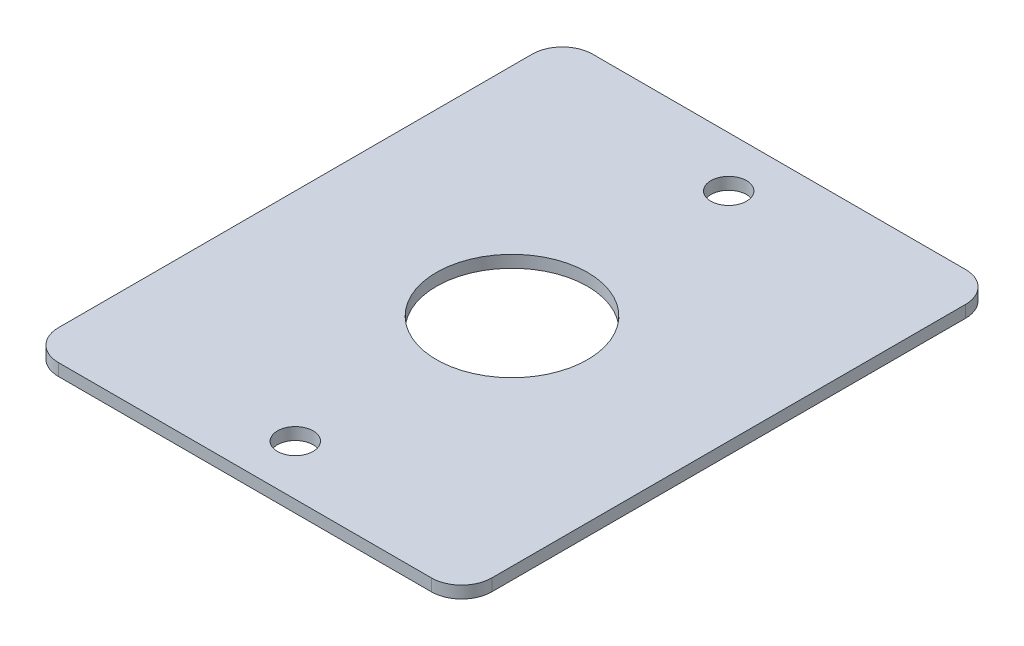
SolidWorks part; units mm, degrees
material "6061-T6 (SS)"
ref_plane "Front Plane" through (0, 0, 0) normal (0, 0, 1) x (1, 0, 0)
ref_plane "Top Plane" through (0, 0, 0) normal (0, 1, 0) x (1, 0, 0)
ref_plane "Right Plane" through (0, 0, 0) normal (1, 0, 0) x (0, 0, -1)
sketch "Sketch1" plane through (0, 0, 0) normal (0, 1, 0) x (1, 0, 0)
  line L0 (-27.305, 33.655) -> (-27.305, -33.655)
  line L1 (-27.305, 33.655) -> (27.305, 33.655)
  line L2 (-27.305, -33.655) -> (27.305, -33.655)
  line L3 (27.305, 33.655) -> (27.305, -33.655)
  line L4 (-27.305, -33.655) -> (27.305, 33.655) construction
  line L5 (0, -27.305) -> (0, 27.305) construction
  circle A0 centre (0, 0) radius 9.525
  circle A1 centre (0, 27.305) radius 2.2479
  circle A2 centre (0, -27.305) radius 2.2479
  dimension "D1" = 19.05
  dimension "D4" = 4.4958
  dimension "D2" = 54.61
  dimension "D3" = 67.31
  dimension "D5" = 6.35
extrude "Boss-Extrude1" add sketch "Sketch1" along normal blind 1.524
fillet "Fillet1" radius 3.81 4 edges at (27.305, 0.762, -33.655) (27.305, 0.762, 33.655) (-27.305, 0.762, -33.655) (-27.305, 0.762, 33.655)
